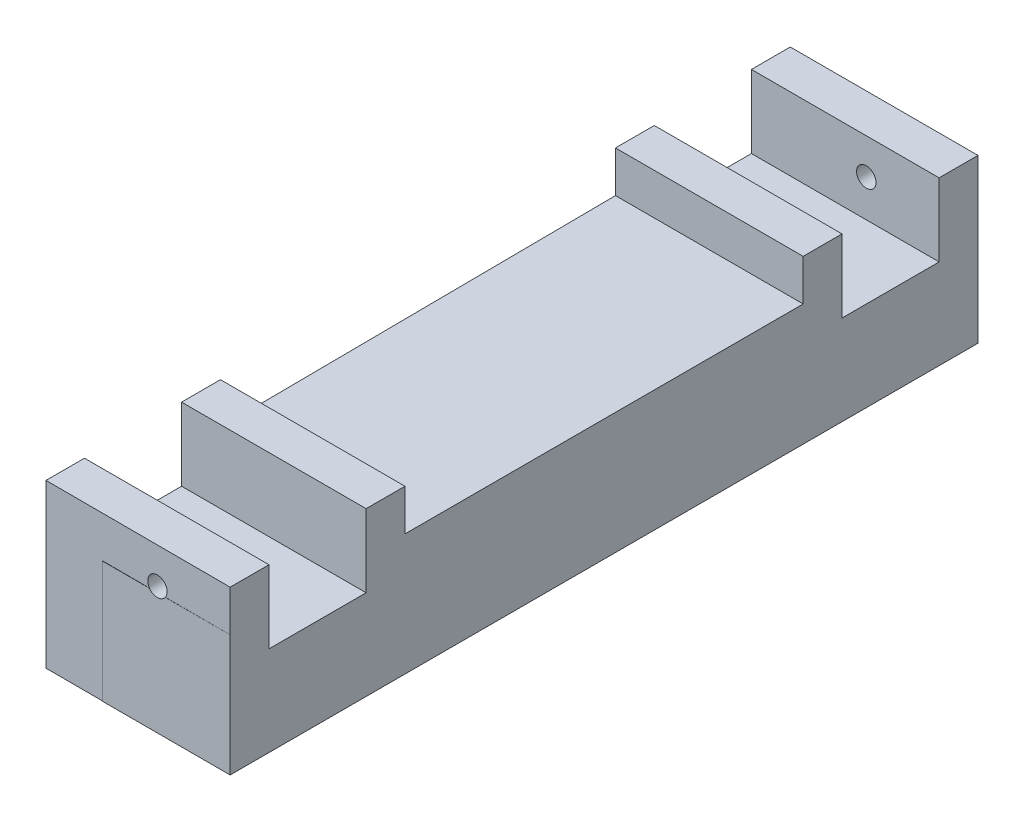
SolidWorks part; units mm, degrees
material "ABS"
ref_plane "前视基准面" through (0, 0, 0) normal (0, 0, 1) x (1, 0, 0)
ref_plane "上视基准面" through (0, 0, 0) normal (0, 1, 0) x (1, 0, 0)
ref_plane "右视基准面" through (0, 0, 0) normal (1, 0, 0) x (0, 0, -1)
other "Configuration Table"
sketch "草图1" plane through (0, 0, 0) normal (1, 0, 0) x (0, 0, -1)
  line L0 (-20.2558, 11.348) -> (-20.2558, -3.652)
  line L1 (-20.2558, -3.652) -> (-0.2558, -3.652)
  line L2 (-0.2558, -3.652) -> (-0.2558, 11.348)
  line L3 (-0.2558, 11.348) -> (97.7442, 11.348)
  line L4 (97.7442, 11.348) -> (97.7442, -3.652)
  line L5 (97.7442, -3.652) -> (117.7442, -3.652)
  line L6 (117.7442, -3.652) -> (117.7442, 11.348)
  line L7 (117.7442, 11.348) -> (125.7442, 11.348)
  line L8 (125.7442, 11.348) -> (125.7442, -13.652)
  line L9 (125.7442, -13.652) -> (-28.2558, -13.652)
  line L10 (-28.2558, -13.652) -> (-28.2558, 11.348)
  line L11 (-28.2558, 11.348) -> (-20.2558, 11.348)
  dimension "D1" = 15
  dimension "D2" = 8
  dimension "D3" = 98
  dimension "D4" = 10
  dimension "D5" = 20
  dimension "D6" = 8
extrude "凸台-拉伸1" add sketch "草图1" along normal blind 30
sketch "草图2" plane through (0, 0, 0) normal (-1, 0, 0) x (0, 0, 1)
  line L0 (-117.7442, -3.652) -> (-117.7442, 11.348)
  line L2 (-117.7442, -3.652) -> (-117.7442, -13.652)
  line L3 (28.2558, -13.652) -> (-125.7442, -13.652) construction
  line L4 (-117.7442, -13.652) -> (-132.7442, -13.652)
  line L6 (-132.7442, -13.652) -> (-132.7442, 16.348)
  line L7 (-132.7442, 16.348) -> (-117.7442, 16.348)
  line L8 (-117.7442, 16.348) -> (-117.7442, 11.348)
  line L9 (-117.7442, 11.348) -> (53.2558, 11.348)
  line L10 (53.2558, 11.348) -> (53.2558, -13.652)
  line L11 (53.2558, -13.652) -> (-117.7442, -13.652)
  line L12 (53.2558, -3.652) -> (123.2558, -3.652)
  line L13 (123.2558, -3.652) -> (123.2558, -13.652)
  line L14 (123.2558, -13.652) -> (53.2558, -13.652)
  line L15 (28.2558, 11.348) -> (28.2558, -13.652) construction
  line M5 (28.2558, 11.348) -> (20.2558, 11.348)
  line M6 (20.2558, 11.348) -> (20.2558, -3.652)
  line M7 (20.2558, -3.652) -> (0.2558, -3.652)
  line M8 (0.2558, -3.652) -> (0.2558, 11.348)
  line M9 (0.2558, 11.348) -> (-97.7442, 11.348)
  line M10 (-97.7442, 11.348) -> (-97.7442, -3.652)
  line M11 (-97.7442, -3.652) -> (-117.7442, -3.652)
  line M12 (-117.7442, -3.652) -> (-117.7442, 11.348)
  line M13 (-117.7442, 11.348) -> (-125.7442, 11.348)
  line M14 (-125.7442, 11.348) -> (-125.7442, -13.652)
  line M15 (-125.7442, -13.652) -> (28.2558, -13.652)
  line M16 (28.2558, -13.652) -> (28.2558, 11.348)
  dimension "D1" = 15
  dimension "D2" = 30
  dimension "D3" = 70
  dimension "D4" = 95
extrude "凸台-拉伸4" add sketch "草图2" along normal blind 70 contours L8 L7 L6 L4 M14 M13 | L2 M12 M13 M14 M15 | L2 M11 M15 M16 M5 M6 M7 M8 M9 M10 | L9 M12 M11 M10 | L9 M8 M7 M6 | L11 L10 L9 M16 | L14 L13 L12 L10
sketch "草图5" plane through (0, 16.348, 0) normal (0, 1, 0) x (1, 0, 0)
  line L0 (-35, 132.7442) -> (-35, 91.3525) construction
  line L1 (-70, 132.7442) -> (0, 132.7442) construction
  line L2 (-70, 125.2442) -> (42.7288, 125.2442) construction
  line L3 (-70, 132.7442) -> (-70, 117.7442) construction
  circle A0 centre (-51, 125.2442) radius 2.8
  circle A1 centre (-19, 125.2442) radius 2.8
  dimension "D1" = 5.6
  dimension "D2" = 5.6
  dimension "D3" = 32
  dimension "D4" = 16
extrude "切除-拉伸3" cut sketch "草图5" against normal blind 5
sketch "草图6" plane through (0, -3.652, 0) normal (0, 1, 0) x (1, 0, 0)
  line L0 (-35, -123.2558) -> (-35, 217.3926) construction
  line L1 (-70, -123.2558) -> (0, -123.2558) construction
  line L2 (0, -112.3162) -> (-87.989, -112.3162) construction
  line L3 (0, -53.2558) -> (0, -123.2558) construction
  circle A0 centre (-55, -112.3162) radius 2.8
  circle A1 centre (-15, -112.3162) radius 2.8
  dimension "D1" = 5.6
  dimension "D2" = 5.6
  dimension "D3" = 40
  dimension "D4" = 20
extrude "切除-拉伸4" cut sketch "草图6" against normal blind 5
pattern_linear "阵列(线性)1" count 3 spacing 19 along (0, 0, -1) of "切除-拉伸4"
sketch "草图9" plane through (0, 11.348, 0) normal (0, 1, 0) x (1, 0, 0)
  line L0 (-8.6581, 117.7442) -> (-8.6581, 125.7442)
  line L1 (-70, 117.7442) -> (0, 117.7442) construction
  line L2 (-8.6581, 117.7442) -> (-8.6581, 89.7442)
  line L3 (-8.6581, 89.7442) -> (30, 89.7442)
  line L4 (30, 97.7442) -> (30, -0.2558) construction
  line L5 (30, 89.7442) -> (30, 97.7442)
  line L6 (30, 97.7442) -> (0, 97.7442)
  line L7 (0, 97.7442) -> (0, 117.7442)
  line L8 (0, 117.7442) -> (30, 117.7442)
  line L9 (30, 117.7442) -> (30, 125.7442)
  line L10 (30, 125.7442) -> (0, 125.7442)
  line L12 (-8.6581, 125.7442) -> (0, 125.7442)
  dimension "D1" = 8
sketch "草图13" plane through (0, 11.348, 0) normal (0, 1, 0) x (1, 0, 0)
  line L0 (30, -0.2558) -> (30, 7.7442)
  line L1 (30, 89.7442) -> (30, -0.2558) construction
  line L2 (30, 7.7442) -> (-8, 7.7442)
  line L3 (-8, 7.7442) -> (-8, -28.1761)
  line L4 (-8, -28.1761) -> (30, -28.2558)
  line L5 (30, -28.2558) -> (30, -20.2558)
  line L6 (30, -20.2558) -> (0, -20.2558)
  line L7 (0, -20.2558) -> (0, -0.2558)
  line L8 (0, -0.2558) -> (30, -0.2558)
  dimension "D1" = 8
  dimension "D2" = 8
sketch "草图14" plane through (0, -3.652, 0) normal (0, 1, 0) x (1, 0, 0)
  line L0 (30, -0.2558) -> (0, -0.2558)
  line L1 (0, -0.2558) -> (0, -20.2558)
  line L2 (0, -20.2558) -> (30, -20.2558)
  line L3 (30, -20.2558) -> (30, -0.2558)
  line L4 (30, 117.7442) -> (0, 117.7442)
  line L5 (0, 117.7442) -> (0, 97.7442)
  line L6 (0, 117.7442) -> (0, 97.7442) construction
  line L7 (30, 97.7442) -> (0, 97.7442) construction
  line L8 (0, 97.7442) -> (30, 97.7442)
  line L9 (30, 97.7442) -> (30, 117.7442)
extrude "凸台-拉伸16" add sketch "草图14" along normal blind 8.5
extrude "凸台-拉伸17" add sketch "草图9" along normal blind 8.5
extrude "凸台-拉伸18" add sketch "草图13" along normal blind 8.5
sketch "草图15" plane through (0, -3.652, 0) normal (0, 1, 0) x (1, 0, 0)
  line L0 (-70, -123.2558) -> (-210, -123.2558)
  line L1 (-210, -123.2558) -> (-210, 36.7442)
  line L2 (-210, 36.7442) -> (-70, 36.7442)
  line L3 (-70, 117.7442) -> (-70, -53.2558) construction
  line L4 (-70, 36.7442) -> (-70, -123.2558)
  dimension "D1" = 140
  dimension "D2" = 160
extrude "凸台-拉伸21" add sketch "草图15" against normal blind 10
sketch "草图17" plane through (0, -3.652, 0) normal (0, 1, 0) x (1, 0, 0)
  line L0 (-210, 36.7442) -> (-70, 36.7442)
  line L1 (-70, 36.7442) -> (-70, -123.2558)
  line L2 (-210, -123.2558) -> (0, -123.2558) construction
  line L3 (-70, -123.2558) -> (-210, -123.2558)
  line L4 (-210, -123.2558) -> (-210, 36.7442)
extrude "凸台-拉伸22" add sketch "草图17" along normal blind 15
sketch "草图20" plane through (0, 0, -125.7442) normal (0, 0, -1) x (-1, 0, 0)
  line L0 (-30, 19.848) -> (-15, 19.848) construction
  line L1 (-30, 19.848) -> (8.6581, 19.848) construction
  line L2 (-15, 19.848) -> (-15, 12.498) construction
  circle A0 centre (-15, 12.498) radius 2
  dimension "D3" = 4
  dimension "D1" = 15
  dimension "D2" = 7.35
extrude "切除-拉伸8" cut sketch "草图20" against normal up to next
sketch "草图21" plane through (-0.0591, 0, 28.1927) normal (-0.0021, 0, 1) x (1, 0, 0.0021)
  line L0 (30.0592, 19.848) -> (15.0592, 19.848) construction
  line L1 (-7.9409, 19.848) -> (30.0592, 19.848) construction
  line L2 (15.0592, 19.848) -> (15.0592, 12.498) construction
  line L7 (0.0593, 11.348) -> (0.0593, -13.652)
  line L8 (0.0593, -13.652) -> (30.0592, -13.652)
  line L9 (30.0592, -13.652) -> (30.0592, 11.348)
  line L10 (30.0592, 11.348) -> (0.0593, 11.348)
  line L11 (0.0593, 11.348) -> (0.0593, -13.652)
  line L12 (0.0593, -13.652) -> (30.0592, -13.652)
  line L13 (30.0592, -13.652) -> (30.0592, 11.348)
  line L14 (30.0592, 11.348) -> (0.0593, 11.348)
  circle A0 centre (15.0592, 12.498) radius 2
  circle A1 centre (15.0592, 12.498) radius 2
  dimension "D3" = 4
  dimension "D1" = 15
  dimension "D2" = 7.35
  dimension "D4" = 0
extrude "切除-拉伸10" cut sketch "草图21" against normal up to next contours L14 A0
sketch "草图22" plane through (0, 0, 28.2558) normal (0, 0, 1) x (1, 0, 0)
  line L0 (15, 11.348) -> (15, 12.498) construction
  line L1 (30, 11.348) -> (0, 11.348) construction
  circle A0 centre (15, 12.498) radius 2
  dimension "D2" = 4
  dimension "D1" = 1.15
extrude "切除-拉伸11" cut sketch "草图22" against normal up to next
sketch "草图23" plane through (0, 11.348, 0) normal (0, 1, 0) x (1, 0, 0)
  line L0 (-140, -123.2558) -> (-140, 71.7728) construction
  line L1 (-210, -123.2558) -> (-70, -123.2558) construction
  line L2 (-70, -123.2558) -> (-70, -53.2558) construction
  line L3 (-210, -93.2558) -> (78.2311, -93.2558) construction
  line L4 (-210, 36.7442) -> (-210, -123.2558) construction
  circle A0 centre (-194, -93.2558) radius 2.8
  circle A1 centre (-86, -93.2558) radius 2.8
  dimension "D2" = 5.6
  dimension "D3" = 5.6
  dimension "D1" = 30
  dimension "D4" = 108
  dimension "D5" = 16
extrude "切除-拉伸12" cut sketch "草图23" against normal blind 5
sketch "草图24" plane through (0, 11.348, 0) normal (0, 1, 0) x (1, 0, 0)
  line L0 (-140, -123.2558) -> (-140, 120.4111) construction
  line L1 (-210, -123.2558) -> (-70, -123.2558) construction
  line L2 (-210, 26.7442) -> (84.7359, 26.7442) construction
  line L3 (-210, 36.7442) -> (-210, -123.2558) construction
  line L4 (-210, -47.5558) -> (124.7427, -47.5558) construction
  line L5 (-70, 36.7442) -> (-210, 36.7442) construction
  circle A0 centre (-196.5, 26.7442) radius 1.9
  circle A1 centre (-83.5, 26.7442) radius 1.9
  circle A2 centre (-196.5, -47.5558) radius 1.9
  circle A3 centre (-83.5, -47.5558) radius 1.9
  dimension "D2" = 3.8
  dimension "D3" = 3.8
  dimension "D4" = 3.8
  dimension "D5" = 3.8
  dimension "D1" = 74.3
  dimension "D6" = 113
  dimension "D7" = 56.5
  dimension "D8" = 10
extrude "切除-拉伸13" cut sketch "草图24" against normal blind 5
sketch "草图26" plane through (0, 19.848, 0) normal (0, 1, 0) x (1, 0, 0)
  line L0 (-8.6581, 89.7442) -> (-8, 7.7442)
  line L1 (3.2177, 125.7442) -> (3.8024, 150.1925)
  line L2 (3.8024, 150.1925) -> (-171.6126, 166.5259)
  line L3 (-171.6126, 166.5259) -> (-482.1907, -91.1415)
  line L4 (-482.1907, -91.1415) -> (-210.7192, -353.9724)
  line L5 (-210.7192, -353.9724) -> (3.5101, -124.5068)
  line L6 (3.5101, -124.5068) -> (3.7121, -28.2006)
  line L7 (3.7121, -28.2006) -> (-8, -28.1761)
  line L8 (30, 117.7442) -> (30, 125.7442)
  line L9 (30, 125.7442) -> (-8.6581, 125.7442)
  line L10 (-8.6581, 125.7442) -> (-8.6581, 89.7442)
  line L11 (-8.6581, 89.7442) -> (30, 89.7442)
  line L12 (30, 89.7442) -> (30, 97.7442)
  line L13 (30, 97.7442) -> (0, 97.7442)
  line L14 (0, 97.7442) -> (0, 117.7442)
  line L15 (0, 117.7442) -> (30, 117.7442)
  line L16 (30, 117.7442) -> (30, 125.7442)
  line L17 (30, 125.7442) -> (-8.6581, 125.7442)
  line L18 (-8.6581, 125.7442) -> (-8.6581, 89.7442)
  line L19 (-8.6581, 89.7442) -> (30, 89.7442)
  line L20 (30, 89.7442) -> (30, 97.7442)
  line L21 (30, 97.7442) -> (0, 97.7442)
  line L22 (0, 97.7442) -> (0, 117.7442)
  line L23 (0, 117.7442) -> (30, 117.7442)
  line L24 (0, -0.2558) -> (30, -0.2558)
  line L25 (30, -0.2558) -> (30, 7.7442)
  line L26 (30, 7.7442) -> (-8, 7.7442)
  line L27 (-8, 7.7442) -> (-8, -28.1761)
  line L28 (-8, -28.1761) -> (30, -28.2558)
  line L29 (30, -28.2558) -> (30, -20.2558)
  line L30 (30, -20.2558) -> (0, -20.2558)
  line L31 (0, -20.2558) -> (0, -0.2558)
  line L32 (0, -0.2558) -> (30, -0.2558)
  line L33 (30, -0.2558) -> (30, 7.7442)
  line L34 (30, 7.7442) -> (-8, 7.7442)
  line L35 (-8, 7.7442) -> (-8, -28.1761)
  line L36 (-8, -28.1761) -> (30, -28.2558)
  line L37 (30, -28.2558) -> (30, -20.2558)
  line L38 (30, -20.2558) -> (0, -20.2558)
  line L39 (0, -20.2558) -> (0, -0.2558)
  line M18 (30, 125.7442) -> (-8.6581, 125.7442)
  line M19 (-8.6581, 125.7442) -> (-8.6581, 89.7442)
  dimension "D1" = 0
  dimension "D2" = 0
extrude "切除-拉伸16" cut sketch "草图26" against normal through all both and the other way through all contours L35 L0 L1 L2 L3 L4 L5 L6 L7 M19 M18
sketch "草图27" plane through (0, 19.848, 0) normal (0, 1, 0) x (1, 0, 0)
  line L0 (0, 97.7442) -> (-12.7211, 97.7442)
  line L5 (-12.7211, 97.7442) -> (0, 117.7442)
  line L6 (0, 117.7442) -> (-16.8595, 117.7442)
  line L7 (-16.8595, 117.7442) -> (-12.7211, 97.7442)
  line L8 (0, -20.2558) -> (0, -0.2558)
  line L9 (0, -0.2558) -> (-11.2203, -0.2558)
  line L10 (-11.2203, -0.2558) -> (-9.1709, -20.2558)
  line L11 (-9.1709, -20.2558) -> (0, -20.2558)
  line M8 (-8.6581, 125.7442) -> (-8.6581, 89.7442)
  line M12 (0, 97.7442) -> (0, 117.7442)
extrude "切除-拉伸17" cut sketch "草图27" against normal blind 15 contours L10 L11 L8 L9 | L5 L0 M8 M12 | L6 L7 L5 M8 | L5 L6 M8
